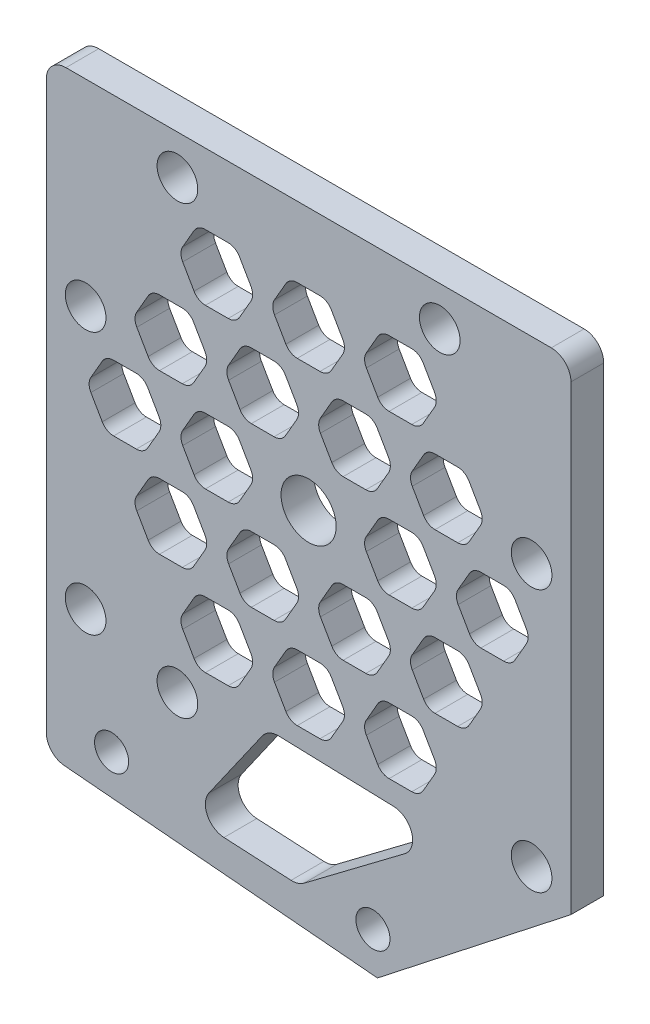
SolidWorks part; units mm, degrees
material "Hexcel AS4C (3000 丝)"
ref_plane "前视基准面" through (0, 0, 0) normal (0, 0, 1) x (1, 0, 0)
ref_plane "上视基准面" through (0, 0, 0) normal (0, 1, 0) x (1, 0, 0)
ref_plane "右视基准面" through (0, 0, 0) normal (1, 0, 0) x (0, 0, -1)
sketch "草图1" plane through (0, 0, 0) normal (0, 0, 1) x (1, 0, 0)
  line L0 (-17, 20) -> (-17, -20) construction
  line L1 (-20, 20) -> (20, 20)
  line L2 (-20, 20) -> (-20, -20)
  line L3 (-20, -20) -> (20, -20)
  line L4 (20, 20) -> (20, -20)
  line L5 (-20, 20) -> (20, -20) construction
  line L6 (-20, -20) -> (20, 20) construction
  line L7 (0, 0) -> (0, 20) construction
  circle A0 centre (-17, 5) radius 1.55
  circle A1 centre (-17, -15) radius 1.55
  circle A2 centre (17, -15) radius 1.55
  circle A3 centre (17, 5) radius 1.55
  point P0 (0, 0)
  dimension "D4" = 5
  dimension "D5" = 3.1
  dimension "D6" = 20
  dimension "D1" = 40
  dimension "D2" = 40
  dimension "D3" = 3
extrude "凸台-拉伸1" add sketch "草图1" along normal blind 2.5
sketch "草图2" plane through (0, 0, 2.5) normal (0, 0, 1) x (1, 0, 0)
  line L13 (0, 0) -> (27.6777, 0) construction
  line L14 (0, 0) -> (34.8553, 3.0494) construction
  line L18 (-20, -20) -> (20, -23.4995) construction
  line L19 (20, -23.4995) -> (20, -20)
  line L20 (-20, -20) -> (20, -20) construction
  line L21 (-20, -20) -> (20, -20)
  line L22 (20, -20) -> (20, 20) construction
  line L23 (-20, -26.0229) -> (20, -29.5225)
  line L24 (20, -23.4995) -> (20, -29.5225)
  line L25 (-20, -26.0229) -> (-20, -20)
  line L26 (-20, 20) -> (-20, -20) construction
  dimension "D1" = 5
  dimension "D2" = 6
  dimension "D3" = 5
extrude "凸台-拉伸2" add sketch "草图2" against normal up to surface (2.5 mm away) up to face at (0, 0, 0)
sketch "草图3" plane through (0, 0, 2.5) normal (0, 0, 1) x (1, 0, 0)
  line L0 (-5.3185, -27.3074) -> (-4.3928, -16.7257) construction
  line L4 (-20, 20) -> (-20, -26.0229) construction
  line L5 (-20, -26.0229) -> (20, -29.5225) construction
  line L6 (-15.019, -23.4472) -> (-20, -23.0115) construction
  line L7 (20, -29.5225) -> (-20, -26.0229) construction
  circle A0 centre (-15.019, -23.4472) radius 1.3
  circle A1 centre (4.9049, -25.1904) radius 1.3
  dimension "D1" = 2.6
  dimension "D2" = 20
  dimension "D3" = 3
  dimension "D4" = 5
extrude "切除-拉伸1" cut sketch "草图3" against normal through all
sketch "草图4" plane through (0, 0, 0) normal (0, 0, -1) x (-1, 0, 0)
  line L0 (0, 0) -> (0, 20) construction
  line L1 (-20, 20) -> (20, 20) construction
  line L2 (-17, -20) -> (17, -20) construction
  line L3 (10, 17) -> (10, -17) construction
  circle A0 centre (10, -17) radius 1.55
  circle A1 centre (10, 17) radius 1.55
  circle A2 centre (-10, -20) radius 1.55 construction
  circle A3 centre (-10, 17) radius 1.55
  dimension "D1" = 3.1
  dimension "D2" = 3
  dimension "D3" = 10
  dimension "D5" = 3
  dimension "D6" = 10
  dimension "D4" = 40
extrude "切除-拉伸2" cut sketch "草图4" against normal through all
sketch "草图5" plane through (0, 0, 0) normal (0, 0, -1) x (-1, 0, 0)
  line L0 (-10.739, -16.417) -> (0.7919, -25.1045)
  line L1 (0.7919, -25.1045) -> (9.1545, -24.6607)
  line L2 (9.1545, -24.6607) -> (3.0788, -15.991)
  line L3 (3.0788, -15.991) -> (-10.739, -16.417)
  circle A0 centre (0, 0) radius 2.1
  dimension "D1" = 4.2
extrude "切除-拉伸3" cut sketch "草图5" against normal through all
fillet "圆角1" radius 1.5 7 edges at (-20, -26.0229, 1.25) (-20, 20, 1.25) (20, 20, 1.25) (-9.1545, -24.6607, 1.25) (-0.7919, -25.1045, 1.25) (-3.0788, -15.991, 1.25) (10.739, -16.417, 1.25)
sketch "草图6" plane through (0, 0, 0) normal (0, 0, -1) x (-1, 0, 0)
  line L0 (-20, -29.5225) -> (18.6307, -26.1427) construction
  line L1 (-20, -29.5225) -> (-20, 18.5) construction
  line L2 (-20, -29.5225) -> (-5.2486, -28.2319)
  line L3 (-20, -29.5225) -> (-20, -16.6736)
  line L4 (-20, -16.6736) -> (-5.2486, -28.2319)
extrude "切除-拉伸4" cut sketch "草图6" against normal through all
sketch "草图8" plane through (0, 0, 0) normal (0, 0, -1) x (-1, 0, 0)
  line L0 (-8.6603, 15) -> (0, 0) construction
  line L1 (8.6603, 15) -> (-8.6603, 15) construction
  line L2 (-8.6603, 15) -> (-17.3205, 0) construction
  line L3 (-17.3205, 0) -> (-8.6603, -15) construction
  line L4 (-8.6603, -15) -> (8.6603, -15) construction
  line L5 (8.6603, -15) -> (17.3205, 0) construction
  line L6 (17.3205, 0) -> (8.6603, 15) construction
  line L7 (0, 0) -> (15, 0) construction
  line L8 (-5.5566, 14.6244) -> (-8.4434, 14.6244)
  line L9 (-8.4434, 14.6244) -> (-9.8868, 12.1244)
  line L10 (-9.8868, 12.1244) -> (-8.4434, 9.6244)
  line L11 (-8.4434, 9.6244) -> (-5.5566, 9.6244)
  line L12 (-5.5566, 9.6244) -> (-4.1132, 12.1244)
  line L13 (-4.1132, 12.1244) -> (-5.5566, 14.6244)
  line L14 (1.4434, 14.6244) -> (-1.4434, 14.6244)
  line L15 (-1.4434, 14.6244) -> (-2.8868, 12.1244)
  line L16 (-2.8868, 12.1244) -> (-1.4434, 9.6244)
  line L17 (-1.4434, 9.6244) -> (1.4434, 9.6244)
  line L18 (1.4434, 9.6244) -> (2.8868, 12.1244)
  line L19 (2.8868, 12.1244) -> (1.4434, 14.6244)
  line L20 (8.4434, 14.6244) -> (5.5566, 14.6244)
  line L21 (5.5566, 14.6244) -> (4.1132, 12.1244)
  line L22 (4.1132, 12.1244) -> (5.5566, 9.6244)
  line L23 (5.5566, 9.6244) -> (8.4434, 9.6244)
  line L24 (8.4434, 9.6244) -> (9.8868, 12.1244)
  line L25 (9.8868, 12.1244) -> (8.4434, 14.6244)
  line L26 (-9.0566, 8.5622) -> (-11.9434, 8.5622)
  line L27 (-11.9434, 8.5622) -> (-13.3868, 6.0622)
  line L28 (-13.3868, 6.0622) -> (-11.9434, 3.5622)
  line L29 (-11.9434, 3.5622) -> (-9.0566, 3.5622)
  line L30 (-9.0566, 3.5622) -> (-7.6132, 6.0622)
  line L31 (-7.6132, 6.0622) -> (-9.0566, 8.5622)
  line L32 (-12.5566, 2.5) -> (-15.4434, 2.5)
  line L33 (-15.4434, 2.5) -> (-16.8868, 0)
  line L34 (-16.8868, 0) -> (-15.4434, -2.5)
  line L35 (-15.4434, -2.5) -> (-12.5566, -2.5)
  line L36 (-12.5566, -2.5) -> (-11.1132, 0)
  line L37 (-11.1132, 0) -> (-12.5566, 2.5)
  line L38 (-2.0566, 8.5622) -> (-4.9434, 8.5622)
  line L39 (-4.9434, 8.5622) -> (-6.3868, 6.0622)
  line L40 (-6.3868, 6.0622) -> (-4.9434, 3.5622)
  line L41 (-4.9434, 3.5622) -> (-2.0566, 3.5622)
  line L42 (-2.0566, 3.5622) -> (-0.6132, 6.0622)
  line L43 (-0.6132, 6.0622) -> (-2.0566, 8.5622)
  line L44 (4.9434, 8.5622) -> (2.0566, 8.5622)
  line L45 (2.0566, 8.5622) -> (0.6132, 6.0622)
  line L46 (0.6132, 6.0622) -> (2.0566, 3.5622)
  line L47 (2.0566, 3.5622) -> (4.9434, 3.5622)
  line L48 (4.9434, 3.5622) -> (6.3868, 6.0622)
  line L49 (6.3868, 6.0622) -> (4.9434, 8.5622)
  line L50 (11.9434, 8.5622) -> (9.0566, 8.5622)
  line L51 (9.0566, 8.5622) -> (7.6132, 6.0622)
  line L52 (7.6132, 6.0622) -> (9.0566, 3.5622)
  line L53 (9.0566, 3.5622) -> (11.9434, 3.5622)
  line L54 (11.9434, 3.5622) -> (13.3868, 6.0622)
  line L55 (13.3868, 6.0622) -> (11.9434, 8.5622)
  line L56 (-5.5566, 2.5) -> (-8.4434, 2.5)
  line L57 (-8.4434, 2.5) -> (-9.8868, 0)
  line L58 (-9.8868, 0) -> (-8.4434, -2.5)
  line L59 (-8.4434, -2.5) -> (-5.5566, -2.5)
  line L60 (-5.5566, -2.5) -> (-4.1132, 0)
  line L61 (-4.1132, 0) -> (-5.5566, 2.5)
  line L62 (1.4434, 2.5) -> (-1.4434, 2.5) construction
  line L63 (-1.4434, 2.5) -> (-2.8868, 0) construction
  line L64 (-2.8868, 0) -> (-1.4434, -2.5) construction
  line L65 (-1.4434, -2.5) -> (1.4434, -2.5) construction
  line L66 (1.4434, -2.5) -> (2.8868, 0) construction
  line L67 (2.8868, 0) -> (1.4434, 2.5) construction
  line L68 (8.4434, 2.5) -> (5.5566, 2.5)
  line L69 (5.5566, 2.5) -> (4.1132, 0)
  line L70 (4.1132, 0) -> (5.5566, -2.5)
  line L71 (5.5566, -2.5) -> (8.4434, -2.5)
  line L72 (8.4434, -2.5) -> (9.8868, 0)
  line L73 (9.8868, 0) -> (8.4434, 2.5)
  line L74 (15.4434, 2.5) -> (12.5566, 2.5)
  line L75 (12.5566, 2.5) -> (11.1132, 0)
  line L76 (11.1132, 0) -> (12.5566, -2.5)
  line L77 (12.5566, -2.5) -> (15.4434, -2.5)
  line L78 (15.4434, -2.5) -> (16.8868, 0)
  line L79 (16.8868, 0) -> (15.4434, 2.5)
  line L80 (-7.6132, -6.0622) -> (-9.0566, -8.5622)
  line L81 (-9.0566, -3.5622) -> (-7.6132, -6.0622)
  line L82 (-11.9434, -3.5622) -> (-9.0566, -3.5622)
  line L83 (-13.3868, -6.0622) -> (-11.9434, -3.5622)
  line L84 (-11.9434, -8.5622) -> (-13.3868, -6.0622)
  line L85 (-9.0566, -8.5622) -> (-11.9434, -8.5622)
  line L86 (-0.6132, -6.0622) -> (-2.0566, -8.5622)
  line L87 (-2.0566, -3.5622) -> (-0.6132, -6.0622)
  line L88 (-4.9434, -3.5622) -> (-2.0566, -3.5622)
  line L89 (-6.3868, -6.0622) -> (-4.9434, -3.5622)
  line L90 (-4.9434, -8.5622) -> (-6.3868, -6.0622)
  line L91 (-2.0566, -8.5622) -> (-4.9434, -8.5622)
  line L92 (6.3868, -6.0622) -> (4.9434, -8.5622)
  line L93 (4.9434, -3.5622) -> (6.3868, -6.0622)
  line L94 (2.0566, -3.5622) -> (4.9434, -3.5622)
  line L95 (0.6132, -6.0622) -> (2.0566, -3.5622)
  line L96 (2.0566, -8.5622) -> (0.6132, -6.0622)
  line L97 (4.9434, -8.5622) -> (2.0566, -8.5622)
  line L98 (13.3868, -6.0622) -> (11.9434, -8.5622)
  line L99 (11.9434, -3.5622) -> (13.3868, -6.0622)
  line L100 (9.0566, -3.5622) -> (11.9434, -3.5622)
  line L101 (7.6132, -6.0622) -> (9.0566, -3.5622)
  line L102 (9.0566, -8.5622) -> (7.6132, -6.0622)
  line L103 (11.9434, -8.5622) -> (9.0566, -8.5622)
  line L104 (9.8868, -12.1244) -> (8.4434, -14.6244)
  line L105 (8.4434, -9.6244) -> (9.8868, -12.1244)
  line L106 (5.5566, -9.6244) -> (8.4434, -9.6244)
  line L107 (4.1132, -12.1244) -> (5.5566, -9.6244)
  line L108 (5.5566, -14.6244) -> (4.1132, -12.1244)
  line L109 (8.4434, -14.6244) -> (5.5566, -14.6244)
  line L110 (2.8868, -12.1244) -> (1.4434, -14.6244)
  line L111 (1.4434, -9.6244) -> (2.8868, -12.1244)
  line L112 (-1.4434, -9.6244) -> (1.4434, -9.6244)
  line L113 (-2.8868, -12.1244) -> (-1.4434, -9.6244)
  line L114 (-1.4434, -14.6244) -> (-2.8868, -12.1244)
  line L115 (1.4434, -14.6244) -> (-1.4434, -14.6244)
  line L116 (-4.1132, -12.1244) -> (-5.5566, -14.6244)
  line L117 (-5.5566, -9.6244) -> (-4.1132, -12.1244)
  line L118 (-8.4434, -9.6244) -> (-5.5566, -9.6244)
  line L119 (-9.8868, -12.1244) -> (-8.4434, -9.6244)
  line L120 (-8.4434, -14.6244) -> (-9.8868, -12.1244)
  line L121 (-5.5566, -14.6244) -> (-8.4434, -14.6244)
  circle A0 centre (0, 0) radius 15 construction
  circle A1 centre (-7, 12.1244) radius 2.5 construction
  dimension "D1" = 30
  dimension "D2" = 5
  dimension "D3" = 14
  dimension "D5" = 7
  dimension "D7" = 7
  dimension "D9" = 7
  dimension "D11" = 7
  dimension "D4" = 3
  dimension "D6" = 3
  dimension "D8" = 4
  dimension "D10" = 5
extrude "切除-拉伸6" cut sketch "草图8" against normal through all
fillet "圆角3" radius 1 108 edges at (-2.8868, 12.1244, 1.25) (-1.4434, 9.6244, 1.25) (1.4434, 9.6244, 1.25) (2.8868, 12.1244, 1.25) (1.4434, 14.6244, 1.25) (-1.4434, 14.6244, 1.25) (4.1132, -12.1244, 1.25) (8.4434, -14.6244, 1.25) (9.8868, -12.1244, 1.25) (8.4434, -9.6244, 1.25) (5.5566, -9.6244, 1.25) (-13.3868, 6.0622, 1.25) (-11.9434, 3.5622, 1.25) (-9.0566, 3.5622, 1.25) (-7.6132, 6.0622, 1.25) (-9.0566, 8.5622, 1.25) (-11.9434, 8.5622, 1.25) (-6.3868, 6.0622, 1.25) (-4.9434, 3.5622, 1.25) (-2.0566, 3.5622, 1.25) (-0.6132, 6.0622, 1.25) (-2.0566, 8.5622, 1.25) (-4.9434, 8.5622, 1.25) (4.1132, 0, 1.25) (5.5566, -2.5, 1.25) (8.4434, -2.5, 1.25) (9.8868, 0, 1.25) (8.4434, 2.5, 1.25) (5.5566, 2.5, 1.25) (11.1132, 0, 1.25) (12.5566, -2.5, 1.25) (15.4434, -2.5, 1.25) (16.8868, 0, 1.25) (15.4434, 2.5, 1.25) (12.5566, 2.5, 1.25) (4.1132, 12.1244, 1.25) (5.5566, 9.6244, 1.25) (8.4434, 9.6244, 1.25) (9.8868, 12.1244, 1.25) (8.4434, 14.6244, 1.25) (5.5566, 14.6244, 1.25) (7.6132, 6.0622, 1.25) (9.0566, 3.5622, 1.25) (11.9434, 3.5622, 1.25) (13.3868, 6.0622, 1.25) (11.9434, 8.5622, 1.25) (9.0566, 8.5622, 1.25) (-9.8868, 12.1244, 1.25) (-8.4434, 9.6244, 1.25) (-5.5566, 9.6244, 1.25) (-4.1132, 12.1244, 1.25) (-5.5566, 14.6244, 1.25) (-8.4434, 14.6244, 1.25) (0.6132, 6.0622, 1.25) (2.0566, 3.5622, 1.25) (4.9434, 3.5622, 1.25) (6.3868, 6.0622, 1.25) (4.9434, 8.5622, 1.25) (2.0566, 8.5622, 1.25) (-2.8868, -12.1244, 1.25) (-1.4434, -14.6244, 1.25) (1.4434, -14.6244, 1.25) (2.8868, -12.1244, 1.25) (1.4434, -9.6244, 1.25) (-1.4434, -9.6244, 1.25) (-9.8868, -12.1244, 1.25) (-8.4434, -14.6244, 1.25) (-5.5566, -14.6244, 1.25) (-4.1132, -12.1244, 1.25) (-5.5566, -9.6244, 1.25) (-8.4434, -9.6244, 1.25) (-13.3868, -6.0622, 1.25) (-11.9434, -8.5622, 1.25) (-9.0566, -8.5622, 1.25) (-7.6132, -6.0622, 1.25) (-9.0566, -3.5622, 1.25) (-11.9434, -3.5622, 1.25) (-6.3868, -6.0622, 1.25) (-4.9434, -8.5622, 1.25) (-2.0566, -8.5622, 1.25) (-0.6132, -6.0622, 1.25) (-2.0566, -3.5622, 1.25) (-4.9434, -3.5622, 1.25) (7.6132, -6.0622, 1.25) (9.0566, -8.5622, 1.25) (11.9434, -8.5622, 1.25) (13.3868, -6.0622, 1.25) (11.9434, -3.5622, 1.25) (9.0566, -3.5622, 1.25) (-9.8868, 0, 1.25) (-8.4434, -2.5, 1.25) (-5.5566, -2.5, 1.25) (-4.1132, 0, 1.25) (-5.5566, 2.5, 1.25) (-8.4434, 2.5, 1.25) (-16.8868, 0, 1.25) (-15.4434, -2.5, 1.25) (-12.5566, -2.5, 1.25) (-11.1132, 0, 1.25) (-12.5566, 2.5, 1.25) (-15.4434, 2.5, 1.25) (0.6132, -6.0622, 1.25) (2.0566, -8.5622, 1.25) (4.9434, -8.5622, 1.25) (6.3868, -6.0622, 1.25) (4.9434, -3.5622, 1.25) (2.0566, -3.5622, 1.25) (5.5566, -14.6244, 1.25)
